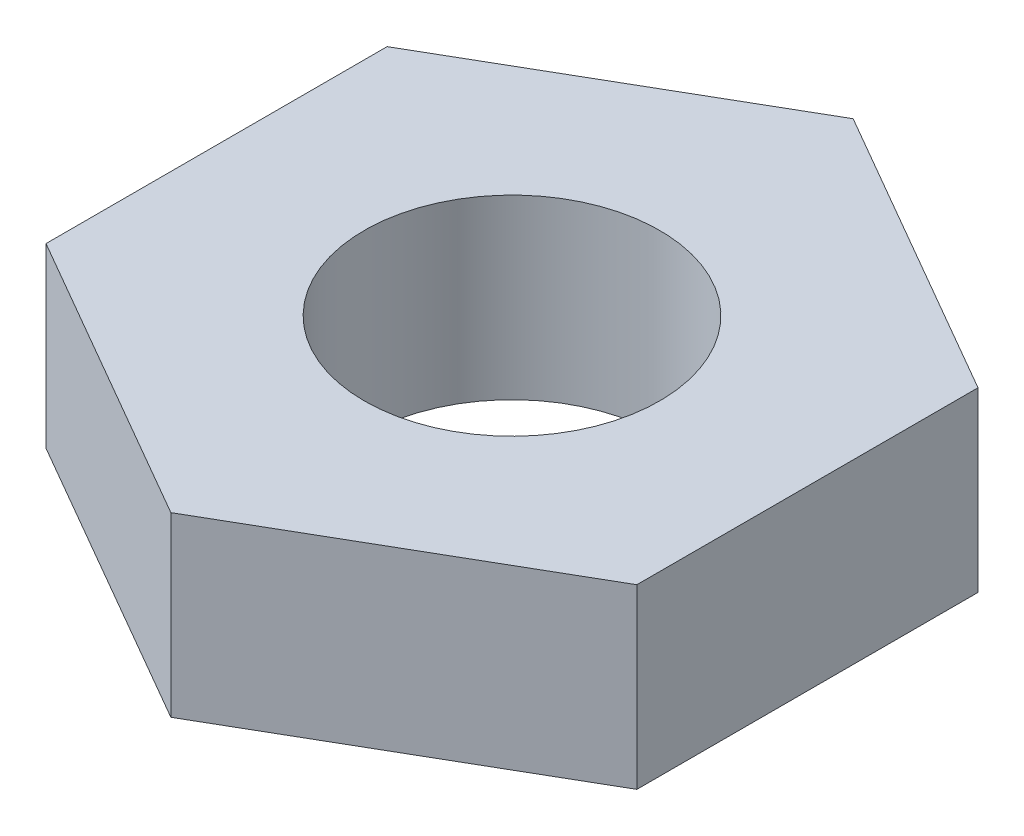
SolidWorks part; units mm, degrees
material "AISI 304"
ref_plane "前视基准面" through (0, 0, 0) normal (0, 0, 1) x (1, 0, 0)
ref_plane "上视基准面" through (0, 0, 0) normal (0, 1, 0) x (1, 0, 0)
ref_plane "右视基准面" through (0, 0, 0) normal (1, 0, 0) x (0, 0, -1)
other "Configuration Table"
sketch "草图1" plane through (0, 0, 0) normal (0, 1, 0) x (1, 0, 0)
  line L1 (0, 2.3094) -> (-2, 1.1547)
  line L2 (-2, 1.1547) -> (-2, -1.1547)
  line L3 (-2, -1.1547) -> (0, -2.3094)
  line L4 (0, -2.3094) -> (2, -1.1547)
  line L5 (2, -1.1547) -> (2, 1.1547)
  line L6 (2, 1.1547) -> (0, 2.3094)
  circle A0 centre (0, 0) radius 1
  circle A1 centre (0, 0) radius 2 construction
  dimension "D1" = 2
  dimension "D2" = 4
extrude "凸台-拉伸1" add sketch "草图1" along normal blind 1.2
